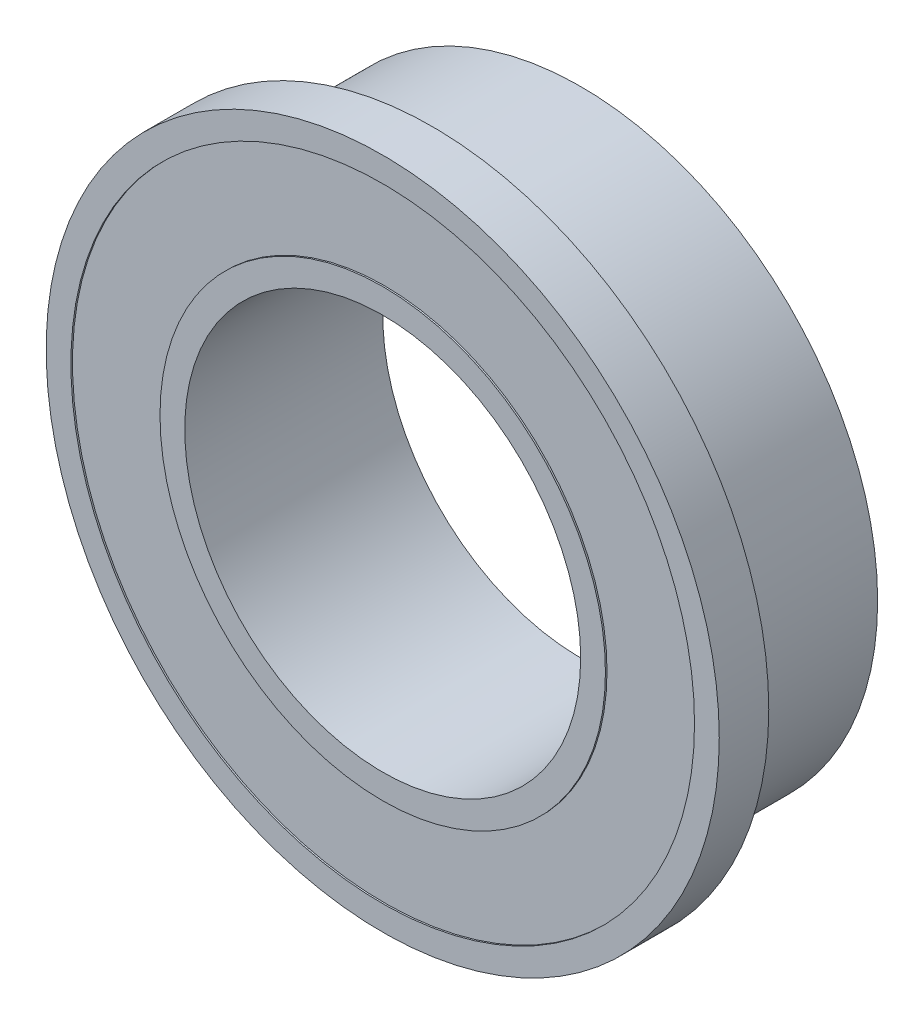
SolidWorks part; units mm, degrees
ref_plane "Front Plane" through (0, 0, 0) normal (0, 0, 1) x (1, 0, 0)
ref_plane "Top Plane" through (0, 0, 0) normal (0, 1, 0) x (1, 0, 0)
ref_plane "Right Plane" through (0, 0, 0) normal (1, 0, 0) x (0, 0, -1)
sketch "Sketch1" plane through (0, 0, 0) normal (0, 0, 1) x (1, 0, 0)
  circle A0 centre (0, 0) radius 3.175
  circle A1 centre (0, 0) radius 4.7625
  dimension "D1" = 6.35
  dimension "D2" = 9.525
extrude "Boss-Extrude1" add sketch "Sketch1" along normal blind 3.175
sketch "Sketch2" plane through (0, 0, 3.175) normal (0, 0, 1) x (1, 0, 0)
  circle A0 centre (0, 0) radius 5.3975
  circle A1 centre (0, 0) radius 4.7625 construction
  circle A2 centre (0, 0) radius 4.7625
  dimension "D1" = 10.795
extrude "Boss-Extrude2" add sketch "Sketch2" against normal blind 0.7937
sketch "Sketch3" plane through (0, 0, 3.175) normal (0, 0, 1) x (1, 0, 0)
  circle A4 centre (0, 0) radius 5.0006
  circle A5 centre (0, 0) radius 5.0006
  circle A7 centre (0, 0) radius 3.5719
  circle A8 centre (0, 0) radius 3.5719
  dimension "D1" = 0.3969
  dimension "D2" = 0.3969
extrude "Cut-Extrude1" cut sketch "Sketch3" against normal blind 0.0254
sketch "Sketch4" plane through (0, 0, 0) normal (0, 0, -1) x (-1, 0, 0)
  circle A2 centre (0, 0) radius 4.3656
  circle A3 centre (0, 0) radius 4.3656
  circle A5 centre (0, 0) radius 3.5719
  circle A6 centre (0, 0) radius 3.5719
  dimension "D1" = 0.3969
  dimension "D2" = 0.3969
extrude "Cut-Extrude2" cut sketch "Sketch4" against normal blind 0.0254
equation "\"D2@Sketch3\"=\"D1@Sketch3\""
equation "\"D1@Sketch4\"=\"D2@Sketch4\""
